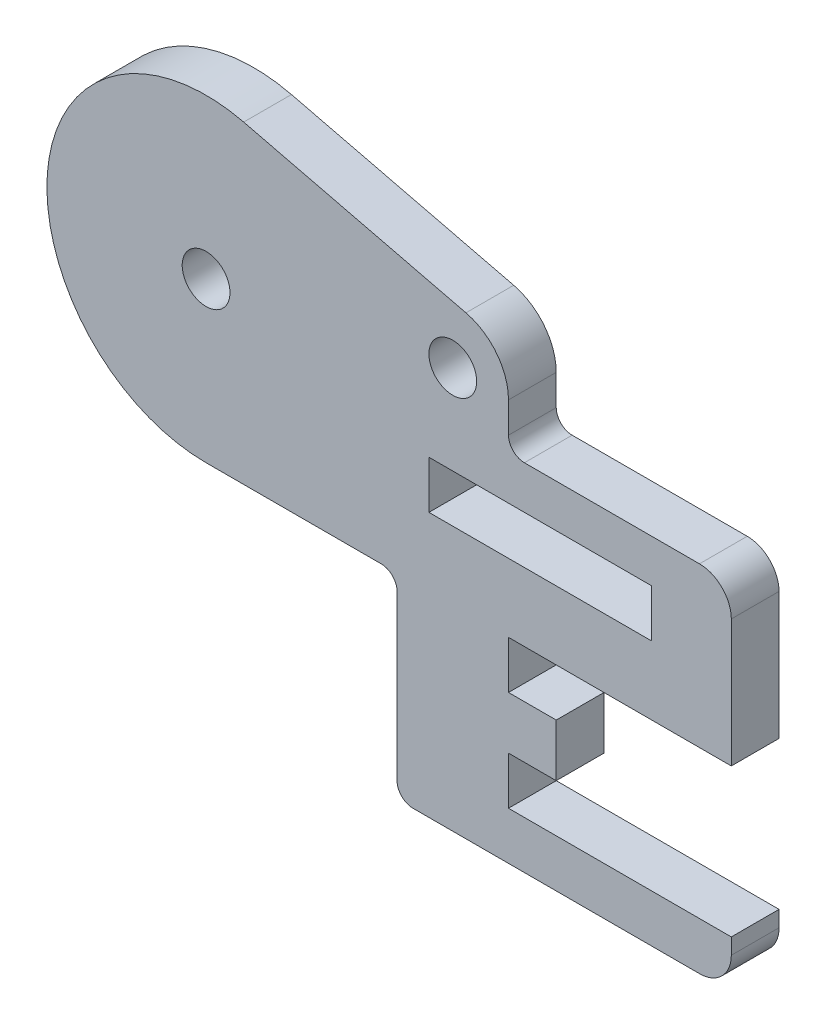
SolidWorks part; units mm, degrees
ref_plane "Front Plane" through (0, 0, 0) normal (0, 0, 1) x (1, 0, 0)
ref_plane "Top Plane" through (0, 0, 0) normal (0, 1, 0) x (1, 0, 0)
ref_plane "Right Plane" through (0, 0, 0) normal (1, 0, 0) x (0, 0, -1)
sketch "Sketch1" plane through (0, 0, 0) normal (0, 0, 1) x (1, 0, 0)
  line L1 (3.8222, -5.1499) -> (3.8222, -23.4499)
  line L2 (1.8222, -25.4499) -> (-16.1778, -25.4499)
  line L4 (-17.1778, -24.4499) -> (-17.1778, -14.1499)
  line L5 (-29.1778, -13.1499) -> (-18.1778, -13.1499)
  line L6 (-9.1778, -3.1499) -> (1.8222, -3.1499)
  line L7 (-10.1778, -2.1499) -> (-10.1778, -0.2299)
  line L8 (-26.8148, 6.5669) -> (-12.8508, 3.171)
  arc A1 (1.8222, -3.1499) -> (3.8222, -5.1499) centre (1.8222, -5.1499) cw
  arc A2 (3.8222, -23.4499) -> (1.8222, -25.4499) centre (1.8222, -23.4499) cw
  arc A6 (-17.1778, -24.4499) -> (-16.1778, -25.4499) centre (-16.1778, -24.4499) ccw
  arc A7 (-18.1778, -13.1499) -> (-17.1778, -14.1499) centre (-18.1778, -14.1499) cw
  arc A11 (-26.8148, 6.5669) -> (-29.1778, -13.1499) centre (-29.1778, -3.1499) ccw
  arc A12 (-9.1778, -3.1499) -> (-10.1778, -2.1499) centre (-9.1778, -2.1499) cw
  arc A13 (-10.1778, -0.2299) -> (-12.8508, 3.171) centre (-13.6778, -0.2299) ccw
  dimension "D4" = 2
  dimension "D5" = 2
  dimension "D6" = 33
  dimension "D7" = 1
  dimension "D9" = 1
  dimension "D3" = 10
  dimension "D8" = 1
  dimension "D11" = 3.5
  dimension "D2" = 14
  dimension "D10" = 18
  dimension "D12" = 10
  dimension "D13" = 22.3
  dimension "D14" = 1.92
extrude "Boss-Extrude1" add sketch "Sketch1" along normal blind 3
sketch "Sketch2" plane through (0, 0, 3) normal (0, 0, 1) x (1, 0, 0)
  circle A0 centre (-29.1778, -3.1499) radius 1.5
  arc A2 (-26.8148, 6.5669) -> (-29.1778, -13.1499) centre (-29.1778, -3.1499) ccw construction
  dimension "D1" = 3
extrude "Cut-Extrude1" cut sketch "Sketch2" against normal blind 3
sketch "Sketch3" plane through (0, 0, 3) normal (0, 0, 1) x (1, 0, 0)
  line L0 (1.8222, -3.1499) -> (-9.1778, -3.1499) construction
  line L1 (-1.1778, -8.8499) -> (-15.1778, -8.8499)
  line L2 (-1.1778, -8.8499) -> (-1.1778, -5.8499)
  line L3 (-1.1778, -5.8499) -> (-15.1778, -5.8499)
  line L4 (-15.1778, -8.8499) -> (-15.1778, -5.8499)
  line L6 (3.8222, -23.4499) -> (3.8222, -5.1499) construction
  line L7 (3.8222, -13.1499) -> (-10.1778, -13.1499)
  line L11 (3.8222, -16.1499) -> (3.8222, -13.1499)
  line L12 (-10.1778, -13.1499) -> (-10.1778, -16.1499)
  line L13 (-10.1778, -16.1499) -> (3.8222, -16.1499)
  line L16 (3.8222, -19.4499) -> (-10.1778, -19.4499)
  line L17 (3.8222, -19.4499) -> (3.8222, -22.4499)
  line L18 (3.8222, -22.4499) -> (-10.1778, -22.4499)
  line L19 (-10.1778, -19.4499) -> (-10.1778, -22.4499)
  dimension "D1" = 14
  dimension "D2" = 3
  dimension "D3" = 2.7
  dimension "D4" = 5
  dimension "D5" = 3
  dimension "D6" = 14
  dimension "D7" = 3
  dimension "D8" = 3.3
  dimension "D9" = 4.3
extrude "Cut-Extrude2" cut sketch "Sketch3" against normal blind 3
sketch "Sketch6" plane through (0, 0, 3) normal (0, 0, 1) x (1, 0, 0)
  circle A0 centre (-13.6778, -0.2299) radius 1.5
  arc A1 (-10.1778, -0.2299) -> (-12.8508, 3.171) centre (-13.6778, -0.2299) ccw construction
  dimension "D1" = 3
extrude "Cut-Extrude5" cut sketch "Sketch6" against normal blind 3
sketch "Sketch7" plane through (0, 0, 3) normal (0, 0, 1) x (1, 0, 0)
  line L0 (3.8222, -19.4499) -> (-10.1778, -19.4499) construction
  line L1 (3.8222, -16.1499) -> (-7.1778, -16.1499)
  line L2 (3.8222, -16.1499) -> (3.8222, -19.4499)
  line L3 (3.8222, -19.4499) -> (-7.1778, -19.4499)
  line L4 (-7.1778, -16.1499) -> (-7.1778, -19.4499)
  dimension "D1" = 11
extrude "Cut-Extrude6" cut sketch "Sketch7" against normal blind 3
